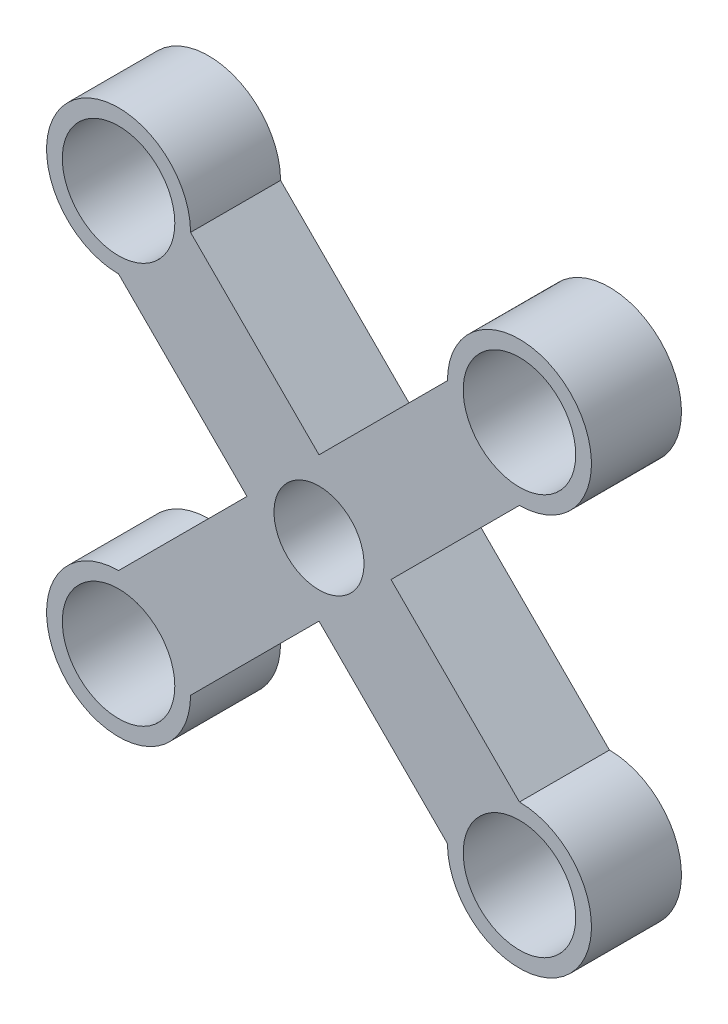
SolidWorks part; units mm, degrees
ref_plane "Front Plane" through (0, 0, 0) normal (0, 0, 1) x (1, 0, 0)
ref_plane "Top Plane" through (0, 0, 0) normal (0, 1, 0) x (1, 0, 0)
ref_plane "Right Plane" through (0, 0, 0) normal (1, 0, 0) x (0, 0, -1)
sketch "Sketch2" plane through (0, 0, 0) normal (0, 0, 1) x (1, 0, 0)
  line L0 (-28.2108, -18.251) -> (-10.0865, -0.1268)
  line L1 (28.3577, 17.9974) -> (10.2335, -0.1268)
  line L2 (28.3577, -18.251) -> (10.2335, -0.1268)
  line L3 (18.1977, -28.411) -> (0.0735, -10.2868)
  line L4 (0.0735, -10.2868) -> (-18.0508, -28.411)
  line L5 (0.0735, 10.0332) -> (-18.0508, 28.1574)
  line L6 (0.0735, 10.0332) -> (18.1977, 28.1574)
  line L7 (-10.0865, -0.1268) -> (-28.2108, 17.9974)
  arc A0 (-18.0508, 28.1574) -> (-28.2108, 17.9974) centre (-28.2108, 28.1574) ccw
  circle A1 centre (0.0735, -0.1268) radius 39.9999 construction
  circle A2 centre (0.0735, -0.1268) radius 39.9999 construction
  arc A3 (28.3577, 17.9974) -> (18.1977, 28.1574) centre (28.3577, 28.1574) ccw
  circle A4 centre (0.0735, -0.1268) radius 39.9999 construction
  arc A5 (18.1977, -28.411) -> (28.3577, -18.251) centre (28.3577, -28.411) ccw
  circle A6 centre (0.0735, -0.1268) radius 39.9999 construction
  arc A7 (-28.2108, -18.251) -> (-18.0508, -28.411) centre (-28.2108, -28.411) ccw
  circle A8 centre (-28.2108, 28.1574) radius 7.9375
  circle A9 centre (28.3577, 28.1574) radius 7.9375
  circle A10 centre (28.3577, -28.411) radius 7.9375
  circle A11 centre (-28.2108, -28.411) radius 7.9375
  circle A12 centre (0.0735, -0.1268) radius 6.35
  circle A13 centre (-28.2108, 28.1574) radius 7.9375 construction
  point P14 (0.0735, -0.1268)
  point P28 (0.0735, -0.1268)
  dimension "D1" = 12.7
extrude "Boss-Extrude1" add sketch "Sketch2" along normal blind 12.7
